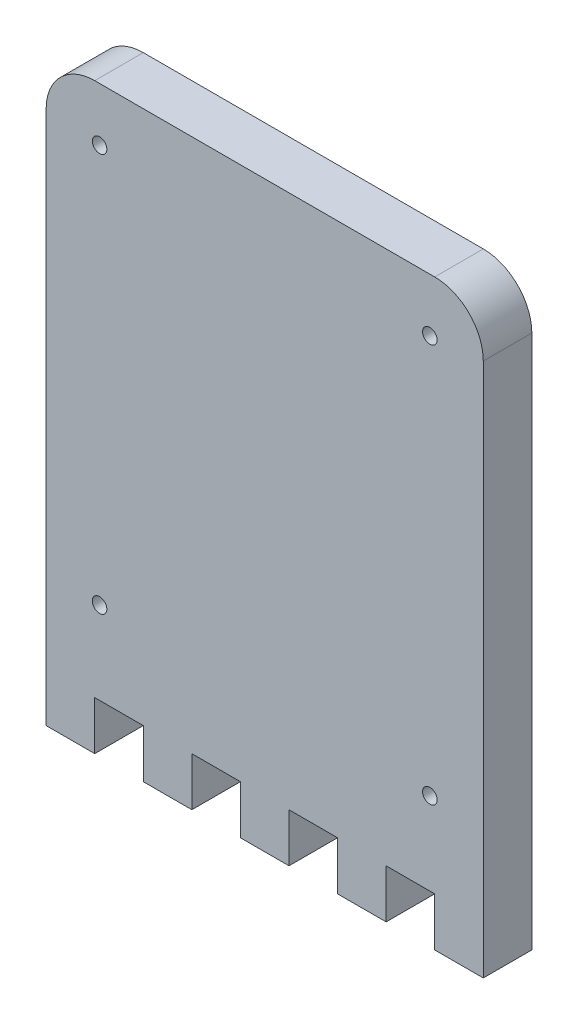
SolidWorks part; units mm, degrees
ref_plane "Спереди" through (0, 0, 0) normal (0, 0, 1) x (1, 0, 0)
ref_plane "Сверху" through (0, 0, 0) normal (0, 1, 0) x (1, 0, 0)
ref_plane "Справа" through (0, 0, 0) normal (1, 0, 0) x (0, 0, -1)
sketch "Эскиз1" plane through (0, 0, 0) normal (0, 0, 1) x (1, 0, 0)
  line L0 (-15, -55) -> (-15, -65)
  line L1 (35, -55) -> (25, -55)
  line L2 (45, -55) -> (45, 45)
  line L3 (35, 55) -> (-35, 55)
  line L4 (-45, -55) -> (-45, 45)
  line L5 (45, -55) -> (-45, 55) construction
  line L6 (45, 55) -> (-45, -55) construction
  line L12 (-45, -55) -> (-45, -65)
  line L13 (-45, -65) -> (-35, -65)
  line L14 (-35, -55) -> (-35, -65)
  line L15 (-25, -65) -> (-15, -65)
  line L16 (-25, -55) -> (-25, -65)
  line L17 (5, -55) -> (5, -65)
  line L18 (-5, -65) -> (5, -65)
  line L19 (-5, -55) -> (-5, -65)
  line L20 (25, -55) -> (25, -65)
  line L21 (15, -65) -> (25, -65)
  line L22 (15, -55) -> (15, -65)
  line L23 (45, -55) -> (45, -65)
  line L24 (35, -65) -> (45, -65)
  line L25 (35, -55) -> (35, -65)
  line L26 (-25, -55) -> (-35, -55)
  line L27 (-5, -55) -> (-15, -55)
  line L28 (15, -55) -> (5, -55)
  arc A0 (45, 45) -> (35, 55) centre (35, 45) ccw
  arc A1 (-35, 55) -> (-45, 45) centre (-35, 45) ccw
  point P0 (0, 0)
  dimension "D3" = 10
  dimension "D1" = 90
  dimension "D2" = 110
  dimension "D4" = 10
  dimension "D5" = 10
  dimension "D6" = 5
extrude "Бобышка-Вытянуть2" add sketch "Эскиз1" along normal mid plane 10
sketch "Эскиз2" plane through (0, 0, 5) normal (0, 0, 1) x (1, 0, 0)
  line L5 (35, 55) -> (-35, 55) construction
  line L6 (40, -44) -> (-40, -44) construction
  line L7 (40, -44) -> (40, 50) construction
  line L8 (40, 50) -> (-40, 50) construction
  line L9 (-40, -44) -> (-40, 50) construction
  line L10 (40, -44) -> (-40, 50) construction
  line L11 (40, 50) -> (-40, -44) construction
  line L12 (45, -65) -> (45, 45) construction
  point P0 (0, 3)
  dimension "D1" = 5
  dimension "D2" = 80
  dimension "D3" = 5
  dimension "D4" = 94
sketch "Эскиз3" plane through (0, 0, 5) normal (0, 0, 1) x (1, 0, 0)
  line L1 (40, 50) -> (-40, 50) construction
  line L3 (-40, -44) -> (-40, 50) construction
  line L4 (0, 0) -> (0, 22.2229) construction
  line L6 (0, 3) -> (-8.2285, 3) construction
  circle A0 centre (-34, 44) radius 1.5
  circle A1 centre (34, 44) radius 1.5
  circle A2 centre (34, -38) radius 1.5
  circle A3 centre (-34, -38) radius 1.5
  dimension "D1" = 6
  dimension "D2" = 6
extrude "Вырез-Вытянуть1" cut sketch "Эскиз3" against normal up to surface (10 mm away) up to face at (0, -40.2663, -5)
